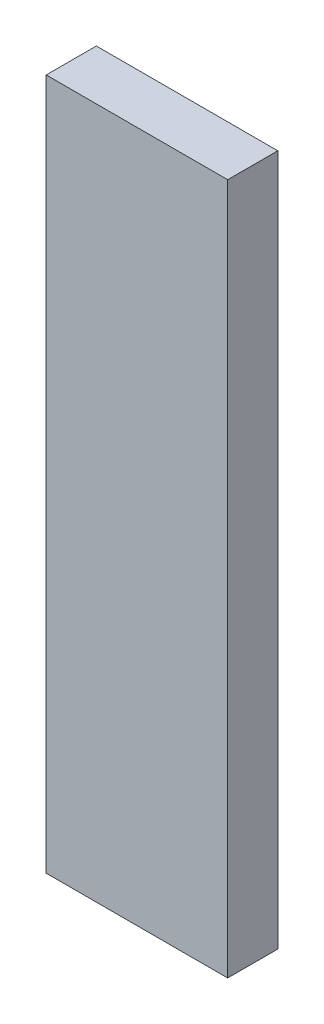
SolidWorks part; units mm, degrees
ref_plane "Front Plane" through (0, 0, 0) normal (0, 0, 1) x (1, 0, 0)
ref_plane "Top Plane" through (0, 0, 0) normal (0, 1, 0) x (1, 0, 0)
ref_plane "Right Plane" through (0, 0, 0) normal (1, 0, 0) x (0, 0, -1)
sketch "Sketch1" plane through (0, 0, 0) normal (0, 1, 0) x (1, 0, 0)
  line L1 (-5.25, -1.45) -> (5.25, -1.45)
  line L2 (-5.25, -1.45) -> (-5.25, 1.45)
  line L3 (-5.25, 1.45) -> (5.25, 1.45)
  line L4 (5.25, -1.45) -> (5.25, 1.45)
  line L5 (-5.25, -1.45) -> (5.25, 1.45) construction
  line L6 (-5.25, 1.45) -> (5.25, -1.45) construction
  point P0 (0, 0)
  dimension "D1" = 2.9
  dimension "D2" = 10.5
extrude "Boss-Extrude1" add sketch "Sketch1" along normal blind 40
